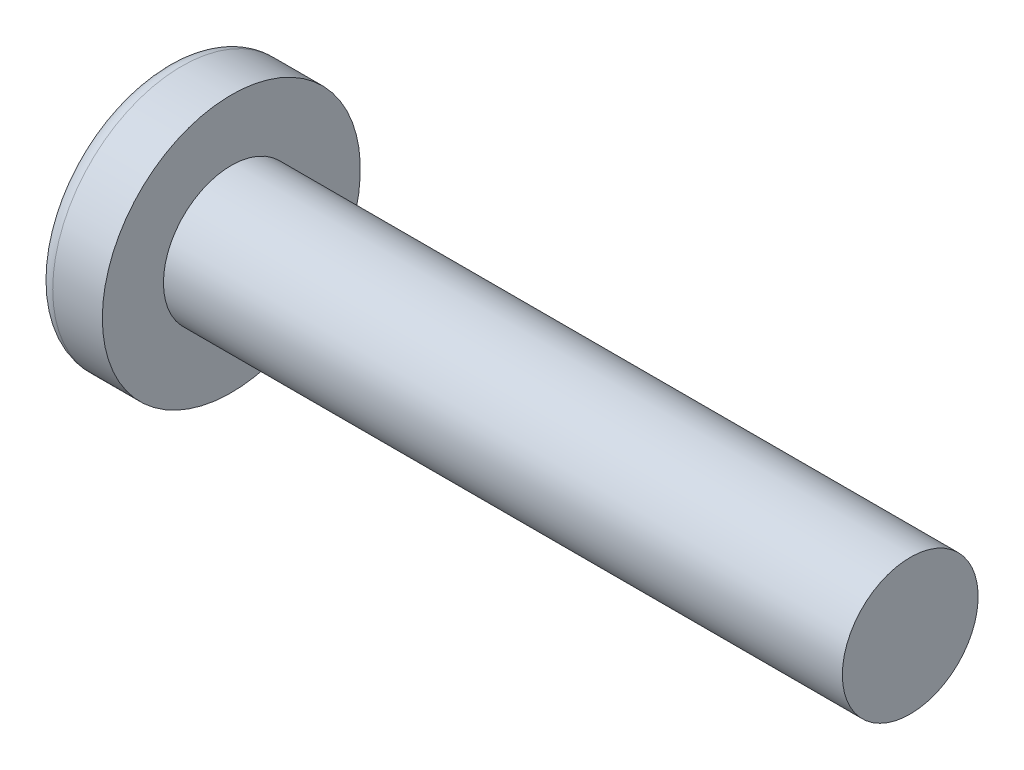
SolidWorks part; units mm, degrees
ref_plane "Plane1" through (0, 0, 0) normal (0, 0, 1) x (1, 0, 0)
ref_plane "Plane2" through (0, 0, 0) normal (0, 1, 0) x (1, 0, 0)
ref_plane "Plane3" through (0, 0, 0) normal (1, 0, 0) x (0, 0, -1)
other "Configuration Table"
sketch "BodySke" plane through (0, 0, 0) normal (0, 0, 1) x (1, 0, 0)
  line L0 (3.7, 2.5) -> (3.7, 4.75)
  line L1 (4.5, 6.35) -> (4.5, -3.175) construction
  line L2 (-25.4, 0) -> (127, 0) construction
  line L3 (28.7, 0) -> (0, 0)
  line L4 (3.7, 2.5) -> (28.7, 2.5)
  line L5 (28.7, 2.5) -> (28.7, 0)
  line L6 (1.8732, 4.75) -> (3.7, 4.75)
  line L7 (3.7, -2.5) -> (28.7, -2.5) construction
  line L8 (3.7, 6.35) -> (3.7, -3.175) construction
  arc A0 (1.3764, 4.4865) -> (0, 0) centre (8, 0) ccw
  arc A2 (1.3764, 4.4865) -> (1.8732, 4.75) centre (1.8732, 4.15) cw
  dimension "Head_crown_rad" = 8
  dimension "Head_fillet_rad" = 0.6
  dimension "Diameter" = 5
  dimension "Length" = 25
  dimension "Head_ht" = 3.7
  dimension "Head_dia" = 9.5
  dimension "Advance" = 0.8
  dimension "Thread_nom" = 25
revolve "Base-Revolve" add sketch "BodySke" angle 360 about L2
cosmetic thread "ThreadCosmetic" [suppressed] parameters "Thread_length"=24.2, "Thread_minor"=4.11
sketch "Sketch3" plane through (0, 0, 0) normal (1, 0, 0) x (0, 0, -1)
  line L0 (0.5, -2.45) -> (-0.5, -2.45)
  line L1 (0.5, -2.45) -> (0.5, 2.45)
  line L2 (-0.5, 2.45) -> (0.5, 2.45)
  line L3 (-0.5, 2.45) -> (-0.5, -2.45)
  dimension "Cross_dia" = 4.9
  dimension "D1" = 2.45
  dimension "Cross_width" = 1
  dimension "D2" = 0.5
ref_plane "Plane4" through (2.95, 0, 0) normal (1, 0, 0) x (0, 0, -1)
sketch "Sketch4" plane through (2.95, 0, 0) normal (1, 0, 0) x (0, 0, -1)
  line L0 (0.25, -0.25) -> (-0.25, -0.25)
  line L1 (0.25, -0.25) -> (0.25, 0.25)
  line L2 (-0.25, 0.25) -> (0.25, 0.25)
  line L3 (-0.25, 0.25) -> (-0.25, -0.25)
  dimension "D2" = 0.5
  dimension "D1" = 0.5
  dimension "D3" = 0.25
  dimension "D4" = 0.25
loft "Cut-Loft1" cut profiles "Sketch3", "Sketch4"
pattern_circular "CirPattern1" count 2 every 90 about axis through (0, 0, 0) along (1, 0, 0) of "Cut-Loft1"
sketch "ThdSchSke" plane through (0, 0, 0) normal (0, 0, 1) x (1, 0, 0)
  line L0 (4.5, -2.055) -> (4.1884, -2.5)
  line L1 (4.5, -2.055) -> (4.8116, -2.5)
  line L2 (4.8116, -2.5) -> (4.8116, -3.125)
  line L3 (-3.175, 0) -> (5.1513, 0) construction
  line L5 (4.8116, -3.125) -> (4.1884, -3.125)
  line L6 (4.1884, -3.125) -> (4.1884, -2.5)
  dimension "Diameter" = 5
  dimension "SideAngle" = 55
  dimension "VeeAngle" = 70
  dimension "Thread_minor" = 4.11
  dimension "Overcut" = 6.25
  dimension "Start" = 4.5
revolve "ThreadSchematic" [suppressed] cut sketch "ThdSchSke" angle 360 about L3
pattern_linear "ThdSchPat" [suppressed]
equation "\"D1@Sketch3\" = \"Cross_dia@Sketch3\" / 2"
equation "\"D2@Sketch3\" = \"Cross_width@Sketch3\" / 2"
equation "\"D1@Sketch4\" = \"Cross_width@Sketch3\" *.5"
equation "\"D2@Sketch4\" = \"D1@Sketch4\""
equation "\"D3@Sketch4\" = \"D1@Sketch4\" / 2"
equation "\"D4@Sketch4\" = \"D2@Sketch4\" / 2"
equation "\"Thread_length@ThreadCosmetic\" = ((sgn( (\"Length@BodySke\" - \"Advance@BodySke\" ) - \"Thread_nom@BodySke\" )-1)*( (\"Length@BodySke\" - \"Advance@BodySke\" ) - \"Thread_nom@BodySke\" ))/-2+ \"Thread_nom@BodySke\""
equation "\"Thread_minor@ThdSchSke\" = \"Thread_minor@ThreadCosmetic\""
equation "\"Diameter@ThdSchSke\" = \"Diameter@BodySke\""
equation "\"Overcut@ThdSchSke\" = \"Diameter@BodySke\" * 1.25"
equation "\"Start@ThdSchSke\" = \"Head_ht@BodySke\" + \"Length@BodySke\" - \"Thread_length@ThreadCosmetic\"  '---Non-countersunk---"
equation "\"Num_threads@ThdSchPat\" = int( \"Thread_length@ThreadCosmetic\" / \"Advance@BodySke\" + 0.999 )  + 1"
equation "\"Advance@ThdSchPat\" = \"Thread_length@ThreadCosmetic\" /  (\"Num_threads@ThdSchPat\" - 1) 'relax it"
